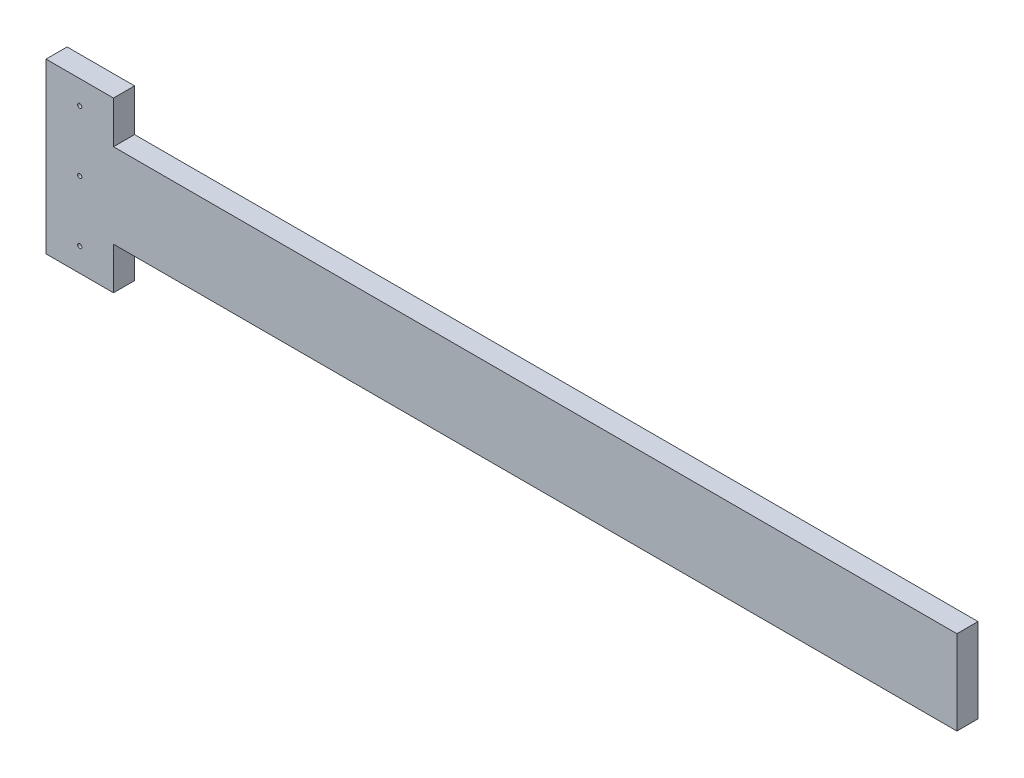
SolidWorks part; units mm, degrees
ref_plane "Front Plane" through (0, 0, 0) normal (0, 0, 1) x (1, 0, 0)
ref_plane "Top Plane" through (0, 0, 0) normal (0, 1, 0) x (1, 0, 0)
ref_plane "Right Plane" through (0, 0, 0) normal (1, 0, 0) x (0, 0, -1)
sketch "Sketch1" plane through (0, 0, 0) normal (0, 0, 1) x (1, 0, 0)
  line L0 (0, -55) -> (0, 55) construction
  line L1 (0, 0) -> (20.32, 0)
  line L2 (0, 0) -> (0, 50.8)
  line L3 (0, 50.8) -> (20.32, 50.8)
  line L4 (20.32, 0) -> (20.32, 12.7)
  line L5 (20.32, 25.4) -> (274.32, 25.4) construction
  line L6 (20.32, 38.1) -> (274.32, 38.1)
  line L8 (20.32, 12.7) -> (274.32, 12.7)
  line L9 (274.32, 38.1) -> (274.32, 12.7)
  line L10 (20.32, 38.1) -> (20.32, 50.8)
  line L11 (10.16, 50.8) -> (10.16, 0) construction
  circle A0 centre (10.16, 43.688) radius 0.635 construction
  circle A1 centre (10.16, 25.4) radius 0.635 construction
  circle A2 centre (10.16, 7.112) radius 0.635 construction
  point P21 (0, 0)
  dimension "D5" = 1.27
  dimension "D1" = 50.8
  dimension "D2" = 20.32
  dimension "D3" = 25.4
  dimension "D4" = 254
  dimension "D6" = 18.288
  dimension "D7" = 18.288
extrude "Boss-Extrude1" add sketch "Sketch1" along normal blind 6.35
sketch "Sketch2" plane through (0, 0, 6.35) normal (0, 0, 1) x (1, 0, 0)
  circle A0 centre (10.16, 43.688) radius 0.635 construction
  circle A1 centre (10.16, 25.4) radius 0.635 construction
  circle A2 centre (10.16, 7.112) radius 0.635 construction
  circle A3 centre (10.16, 43.688) radius 0.635
  circle A4 centre (10.16, 25.4) radius 0.635
  circle A5 centre (10.16, 7.112) radius 0.635
extrude "Cut-Extrude1" cut sketch "Sketch2" against normal through all both and the other way through all
